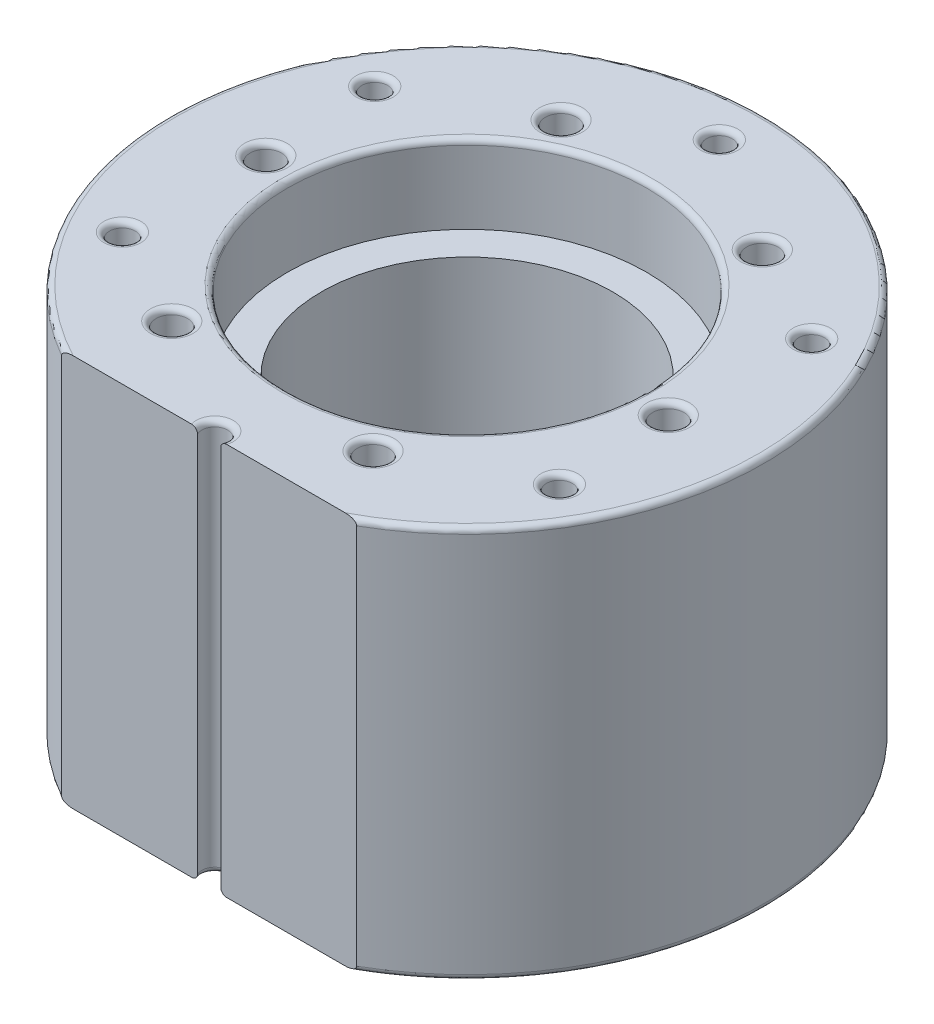
SolidWorks part; units mm, degrees
ref_plane "Front Plane" through (0, 0, 0) normal (0, 0, 1) x (1, 0, 0)
ref_plane "Top Plane" through (0, 0, 0) normal (0, 1, 0) x (1, 0, 0)
ref_plane "Right Plane" through (0, 0, 0) normal (1, 0, 0) x (0, 0, -1)
sketch "Sketch1" plane through (0, 0, 0) normal (0, 0, 1) x (1, 0, 0)
  line L0 (0, 0) -> (0, 13.3508) construction
  line L1 (16.025, 35) -> (26.5, 35)
  line L2 (26.5, 35) -> (26.5, 0)
  line L3 (26.5, 0) -> (13, 0)
  line L4 (16.025, 35) -> (16.025, 28)
  line L5 (16.025, 28) -> (13, 28)
  line L6 (13, 28) -> (13, 0)
  dimension "D1" = 53
  dimension "D2" = 32.05
  dimension "D3" = 26
  dimension "D4" = 35
  dimension "D5" = 7
revolve "Revolve1" add sketch "Sketch1" angle 360 about L0
sketch "Sketch2" plane through (0, 35, 0) normal (0, 1, 0) x (1, 0, 0)
  circle A2 centre (-8.5905, 16.9751) radius 1.4
  circle A3 centre (10.4056, 15.9271) radius 1.4
  circle A4 centre (18.9961, -1.048) radius 1.4
  circle A5 centre (8.5905, -16.9751) radius 1.4
  circle A6 centre (-10.4056, -15.9271) radius 1.4
  circle A7 centre (-18.9961, 1.048) radius 1.4
  circle A8 centre (0, 0) radius 19.025 construction
  circle A9 centre (-8.5905, 16.9751) radius 1.6 construction
  circle A10 centre (-8.5905, 16.9751) radius 1.6 construction
  point P16 (0, 0)
  dimension "D1" = 2.8
  dimension "D2" = 6
extrude "Cut-Extrude1" cut sketch "Sketch2" against normal blind 20
sketch "Sketch4" plane through (0, 0, 0) normal (0, -1, 0) x (1, 0, 0)
  circle A0 centre (0, 0) radius 22.5 construction
  circle A1 centre (0, 22.5) radius 1.15
  circle A2 centre (19.4856, 11.25) radius 1.15
  circle A3 centre (19.4856, -11.25) radius 1.15
  circle A4 centre (0, -22.5) radius 1.15
  circle A5 centre (-19.4856, -11.25) radius 1.15
  circle A6 centre (-19.4856, 11.25) radius 1.15
  point P17 (0, 0)
  dimension "D1" = 45
  dimension "D2" = 2.3
  dimension "D3" = 6
extrude "Cut-Extrude2" cut sketch "Sketch4" against normal through all
fillet "Fillet1" radius 0.5 22 edges at (0, 0, -13) (0, 0, -26.5) (19.4856, 0, 10.1) (19.4856, 0, -12.4) (0, 0, -23.65) (-19.4856, 0, -12.4) (-19.4856, 0, 10.1) (0, 0, 21.35) (0, 35, -26.5) (0, 35, -16.025) (-8.5905, 35, -15.5751) (10.4056, 35, -14.5271) (18.9961, 35, 2.448) (8.5905, 35, 18.3751) (-10.4056, 35, 17.3271) (-18.9961, 35, 0.352) (19.4856, 35, 10.1) (19.4856, 35, -12.4) (0, 35, -23.65) (-19.4856, 35, -12.4) (-19.4856, 35, 10.1) (0, 35, 21.35)
sketch "Sketch6" plane through (0, 35, 0) normal (0, 1, 0) x (1, 0, 0)
  line L1 (61.3311, -32.6332) -> (-59.7715, -32.6332)
  line L2 (61.3311, -32.6332) -> (61.3311, -23)
  line L3 (61.3311, -23) -> (-59.7715, -23)
  line L4 (-59.7715, -32.6332) -> (-59.7715, -23)
  dimension "D1" = 23
extrude "Cut-Extrude3" cut sketch "Sketch6" against normal through all
